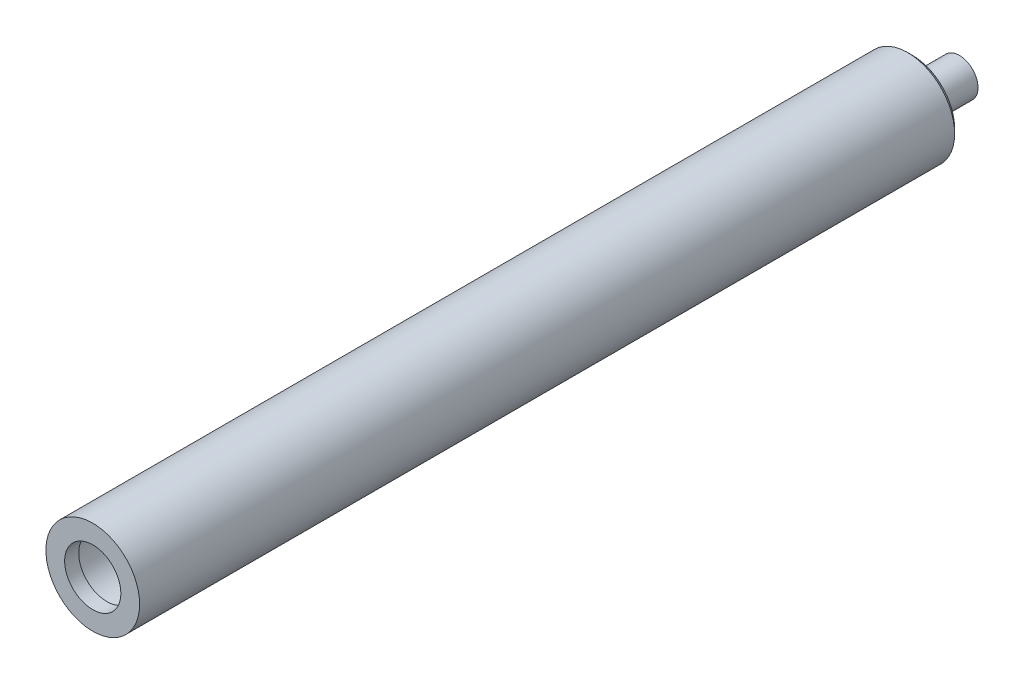
SolidWorks part; units mm, degrees
ref_plane "前视基准面" through (0, 0, 0) normal (0, 0, 1) x (1, 0, 0)
ref_plane "上视基准面" through (0, 0, 0) normal (0, 1, 0) x (1, 0, 0)
ref_plane "右视基准面" through (0, 0, 0) normal (1, 0, 0) x (0, 0, -1)
sketch "草图1" plane through (0, 0, 0) normal (0, 0, 1) x (1, 0, 0)
  circle A0 centre (0, 0) radius 10
  dimension "D1" = 20
extrude "凸台-拉伸1" add sketch "草图1" along normal blind 175
sketch "草图2" plane through (0, 0, 175) normal (0, 0, 1) x (1, 0, 0)
  circle A0 centre (0, 0) radius 7
  dimension "D1" = 14
extrude "切除-拉伸1" cut sketch "草图2" against normal blind 167 contours A0
sketch "草图3" plane through (0, 0, 0) normal (0, 0, -1) x (-1, 0, 0)
  circle A0 centre (0, 0) radius 4
  dimension "D1" = 8
extrude "凸台-拉伸2" add sketch "草图3" along normal blind 10
chamfer "倒角1" distance 1 angle 45 1 edges at (10, 0, 0)
sketch "草图4" plane through (0, 0, 175) normal (0, 0, 1) x (1, 0, 0)
  circle A0 centre (0, 0) radius 7
  circle A1 centre (0, 0) radius 6
  dimension "D1" = 12
extrude "凸台-拉伸3" add sketch "草图4" against normal blind 3
